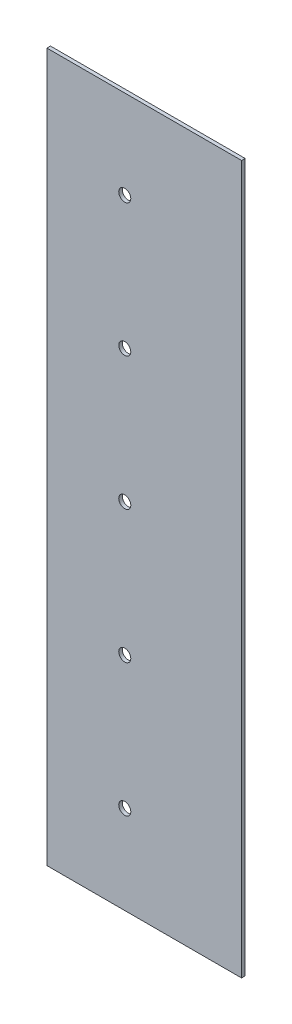
SolidWorks part; units mm, degrees
material "Простая углеродистая сталь"
ref_plane "Спереди" through (0, 0, 0) normal (0, 0, 1) x (1, 0, 0)
ref_plane "Сверху" through (0, 0, 0) normal (0, 1, 0) x (1, 0, 0)
ref_plane "Справа" through (0, 0, 0) normal (1, 0, 0) x (0, 0, -1)
sketch "Эскиз1" plane through (0, 0, 0) normal (0, 0, 1) x (1, 0, 0)
  line L1 (0, 0) -> (55, 0)
  line L2 (0, 0) -> (0, 200)
  line L3 (0, 200) -> (55, 200)
  line L4 (55, 0) -> (55, 200)
  dimension "D1" = 200
  dimension "D2" = 55
extrude "Бобышка-Вытянуть1" add sketch "Эскиз1" along normal blind 1
hole_wizard "Отверстие с зазором M31" positions "Эскиз3" profile "Эскиз2" hole size "M3" standard "DIN"
sketch "Эскиз3" plane through (0, 0, 0) normal (0, 0, -1) x (-1, 0, 0)
  line L0 (-55, 0) -> (-55, 200) construction
  line L1 (-55, 200) -> (0, 200) construction
  point P0 (-22, 175)
  point P11 (-22, 137.5)
  point P12 (-22, 100)
  point P13 (-22, 62.5)
  point P14 (-22, 25)
  dimension "D1" = 33
  dimension "D2" = 25
  dimension "D4" = 37.5
  dimension "D3" = 5
sketch "Эскиз2" plane through (22, 175, 0) normal (1, 0, 0) x (0, 1, 0)
  line L0 (0, 0) -> (0, 6.0215)
  line L1 (0, 6.0215) -> (1.7, 5)
  line L2 (1.7, 5) -> (1.7, 0)
  line L5 (1.7, 0) -> (0, 0)
  line L10 (0, 6.0215) -> (-1.7, 5) construction
  line L11 (0, -6.35) -> (0, 107.95) construction
  dimension "Диаметр отверстия" = 3.4
  dimension "Глубина отверстия" = 5
  dimension "Угол заточки сверла" = 118
